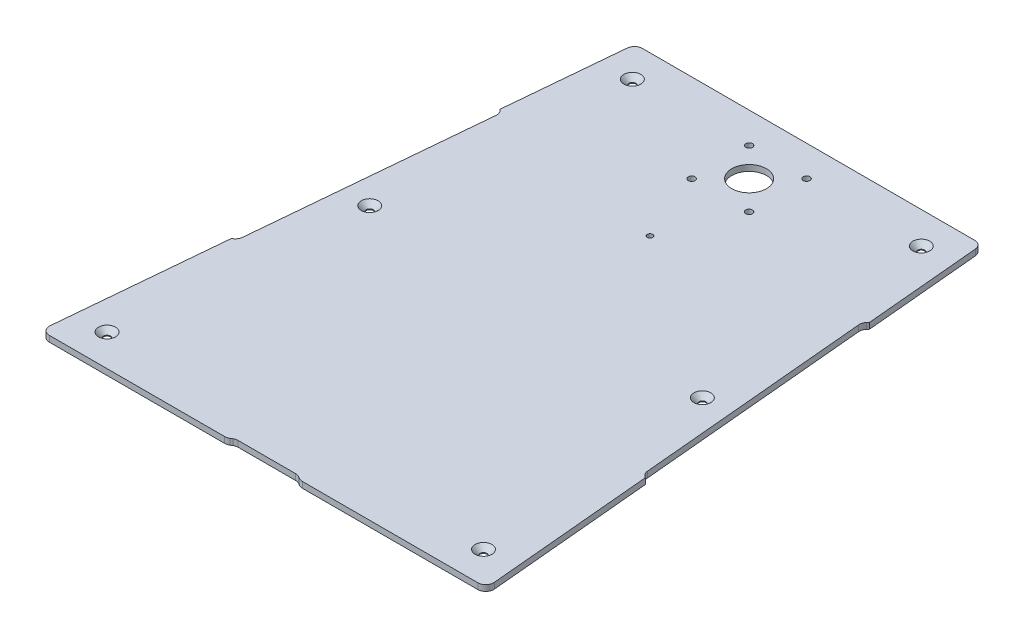
SolidWorks part; units mm, degrees
ref_plane "Front Plane" through (0, 0, 0) normal (0, 0, 1) x (1, 0, 0)
ref_plane "Top Plane" through (0, 0, 0) normal (0, 1, 0) x (1, 0, 0)
ref_plane "Right Plane" through (0, 0, 0) normal (1, 0, 0) x (0, 0, -1)
sketch "Sketch1" plane through (0, 0, 0) normal (0, 1, 0) x (1, 0, 0)
  line L0 (-175, 275) -> (-225, -275)
  line L1 (-225, -275) -> (225, -275)
  line L2 (225, -275) -> (175, 275)
  line L3 (175, 275) -> (-175, 275)
  line L4 (0, -275) -> (0, 275) construction
  line L5 (-200, 0) -> (200, 0) construction
  line L6 (-145.7771, 243) -> (-189.9589, -243) construction
  line L7 (-189.9589, -243) -> (189.9589, -243) construction
  line L8 (189.9589, -243) -> (145.7771, 243) construction
  line L9 (145.7771, 243) -> (-145.7771, 243) construction
  circle A0 centre (0, 215) radius 17.5
  circle A1 centre (-145.7771, 243) radius 3.4
  circle A2 centre (145.7771, 243) radius 3.4
  circle A5 centre (-189.9589, -243) radius 3.4
  circle A6 centre (189.9589, -243) radius 3.4
  circle A7 centre (-167.868, 0) radius 3.4
  circle A8 centre (167.868, 0) radius 3.4
  circle A9 centre (0, 115) radius 2.731
  point P8 (0, 0)
  point P12 (0, 0)
  dimension "D3" = 35
  dimension "D5" = 6.8
  dimension "D8" = 6.8
  dimension "D12" = 5.4621
  dimension "D1" = 350
  dimension "D2" = 550
  dimension "D4" = 60
  dimension "D10" = 450
  dimension "D11" = 100
  dimension "D13" = 32
extrude "Boss-Extrude1" add sketch "Sketch1" against normal blind 6
fillet "Fillet1" radius 8 4 edges at (225, -3, 275) (-225, -3, 275) (175, -3, -275) (-175, -3, -275)
extrude "Cut-Extrude4" cut sketch "Sketch5" against normal blind 20
sketch "Sketch5" plane through (0, 0, 377.3339) normal (0, 1, 0) x (0, 0, 1)
  line L0 (-592.3339, 0) -> (-592.3339, 41) construction
  line L1 (-592.3339, 0) -> (-520.1613, 72.1726) construction
  circle A7 centre (-563.3425, 28.9914) radius 3.4
  circle A8 centre (-563.3425, -28.9914) radius 3.4
  circle A9 centre (-621.3253, -28.9914) radius 3.4
  circle A10 centre (-621.3253, 28.9914) radius 3.4
  point P12 (-592.3339, 0)
  point P13 (-539.2171, 0)
  point P14 (-592.3339, 0)
  point P15 (-514.4105, -0.115)
  point P19 (-592.3339, 0)
  dimension "D3" = 6.8
  dimension "D2" = 45
  dimension "D4" = 41
  dimension "D5" = 4
sketch "Sketch6" plane through (0, 0, 0) normal (0, 1, 0) x (1, 0, 0)
  line L0 (0, 275) -> (0, -275) construction
  line L1 (167.6943, 275) -> (-167.6943, 275) construction
  line L2 (-216.2397, -275) -> (216.2397, -275) construction
  line L3 (199.9342, 0.7243) -> (-199.9342, 0.7243) construction
  line L4 (224.2069, -266.2757) -> (175.6614, 267.7243) construction
  line L5 (-175.6614, 267.7243) -> (-224.2069, -266.2757) construction
  line L6 (-204.632, -95.1331) -> (-182.7223, 145.8731)
  line L7 (-204.632, -95.1331) -> (-218.4599, -106.6564)
  line L8 (-182.7223, 145.8731) -> (-194.2456, 159.7011)
  line L9 (-218.4599, -106.6564) -> (-194.2456, 159.7011)
  point P13 (-124.3469, 2.1706)
  dimension "D1" = 18
  dimension "D2" = 242
  dimension "D3" = 135
  dimension "D4" = 4
extrude "Cut-Extrude5" cut sketch "Sketch6" against normal blind 10
sketch "Sketch7" plane through (0, 0, 0) normal (0, 1, 0) x (1, 0, 0)
  line L0 (0, 275) -> (0, -275) construction
  line L1 (167.6943, 275) -> (-167.6943, 275) construction
  line L2 (-216.2397, -275) -> (216.2397, -275) construction
  line L4 (-31.3206, -271.5943) -> (31.3206, -271.5943)
  line L5 (-31.3206, -271.5943) -> (-45, -279.8932)
  line L6 (-45, -279.8932) -> (45, -279.8932)
  line L7 (31.3206, -271.5943) -> (45, -279.8932)
  line L8 (-31.3206, -271.5943) -> (45, -279.8932) construction
  line L9 (-45, -279.8932) -> (31.3206, -271.5943) construction
  dimension "D1" = 90
  dimension "D2" = 16
extrude "Cut-Extrude6" cut sketch "Sketch7" against normal blind 10
mirror "Mirror2" about plane through (0, 0, 0) normal (1, 0, 0) of "Cut-Extrude5"
fillet "Fillet2" radius 8 8 edges at (-204.632, -3, 95.1331) (-182.7223, -3, -145.8731) (-36.9344, -3, 275) (-31.3206, -3, 271.5943) (36.9344, -3, 275) (31.3206, -3, 271.5943) (204.632, -3, 95.1331) (182.7223, -3, -145.8731)
chamfer "Chamfer1" distance 5.15 angle 45 6 edges at (-145.7771, 0, -239.6) (189.9589, 0, 239.6) (167.868, 0, -3.4) (-189.9589, 0, 246.4) (-167.868, 0, 3.4) (145.7771, 0, -246.4)
sketch "Sketch9" plane through (0, 0, 0) normal (0, 1, 0) x (1, 0, 0)
  line L0 (0, 275) -> (0, -271.5943) construction
  line L1 (167.6943, 275) -> (-167.6943, 275) construction
  line L2 (29.0836, -271.5943) -> (-29.0836, -271.5943) construction
  line L3 (-193.6771, 25.37) -> (193.6771, 25.37) construction
  line L4 (-204.332, -91.833) -> (-183.0223, 142.573) construction
  line L5 (204.332, -91.833) -> (183.0223, 142.573) construction
  line L6 (-148.0781, 29.9183) -> (-163.4505, -139.1782)
  line L7 (-200.9499, -54.63) -> (200.9499, -54.63) construction
  line L8 (-123.1808, 52.6549) -> (123.1808, 52.6549)
  line L9 (-138.5532, -166.4416) -> (138.5532, -166.4416)
  line L10 (148.0781, 29.9183) -> (163.4505, -139.1782)
  arc A0 (-163.4505, -139.1782) -> (-138.5532, -166.4416) centre (-138.5532, -141.4416) ccw
  arc A1 (-148.0781, 29.9183) -> (-123.1808, 52.6549) centre (-123.1808, 27.6549) cw
  arc A2 (163.4505, -139.1782) -> (138.5532, -166.4416) centre (138.5532, -141.4416) cw
  arc A3 (148.0781, 29.9183) -> (123.1808, 52.6549) centre (123.1808, 27.6549) ccw
  point P14 (-155.7643, -54.63)
  point P21 (-165.929, -166.4416)
  point P24 (-146.0111, 52.6549)
  point P28 (0, -166.4416)
  point P31 (0, 52.6549)
  dimension "D4" = 25
  dimension "D1" = 45
  dimension "D2" = 80
  dimension "D3" = 220
sketch "Sketch10" [suppressed] plane through (0, 0, 94.4754) normal (0, 0, 1) x (1, 0, 0)
  line L0 (-89.3279, 30) -> (-81.3279, 30)
  line L1 (-144.5624, 30) -> (-37.7732, 30) construction
  arc A0 (-89.3279, 30) -> (-81.3279, 30) centre (-85.3279, 33) ccw
  point P5 (-85.3279, 30)
  dimension "D1" = 10
sweep "Cut-Sweep2" [suppressed] cut profiles "Sketch10" path "Sketch9"
